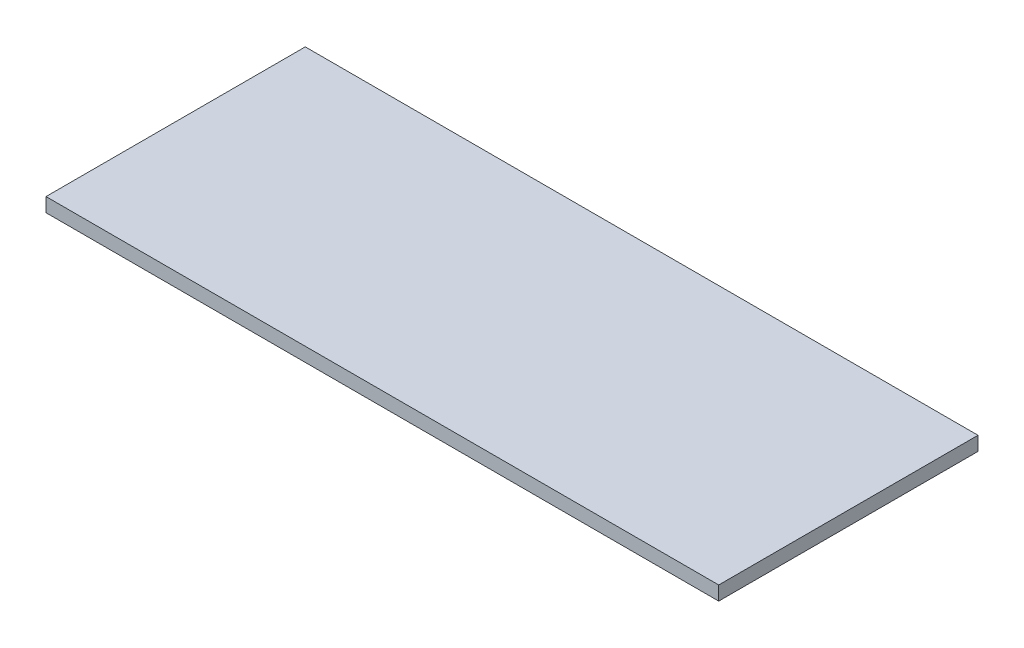
SolidWorks part; units mm, degrees
ref_plane "Front Plane" through (0, 0, 0) normal (0, 0, 1) x (1, 0, 0)
ref_plane "Top Plane" through (0, 0, 0) normal (0, 1, 0) x (1, 0, 0)
ref_plane "Right Plane" through (0, 0, 0) normal (1, 0, 0) x (0, 0, -1)
sketch "Sketch1" plane through (0, 0, 0) normal (0, 1, 0) x (1, 0, 0)
  line L0 (-304.8, -234.95) -> (-304.8, 0) construction
  line L1 (-304.8, -234.95) -> (304.8, -234.95)
  line L2 (-304.8, -234.95) -> (-304.8, 0)
  line L3 (-304.8, 0) -> (304.8, 0)
  line L4 (304.8, -234.95) -> (304.8, 0)
  line L5 (-304.8, -234.95) -> (304.8, 0) construction
  line L6 (-304.8, 0) -> (304.8, -234.95) construction
  line L7 (-292.1, -234.95) -> (-304.8, -234.95) construction
  point P0 (0, -117.475)
extrude "Boss-Extrude1" add sketch "Sketch1" along normal blind 12.7
